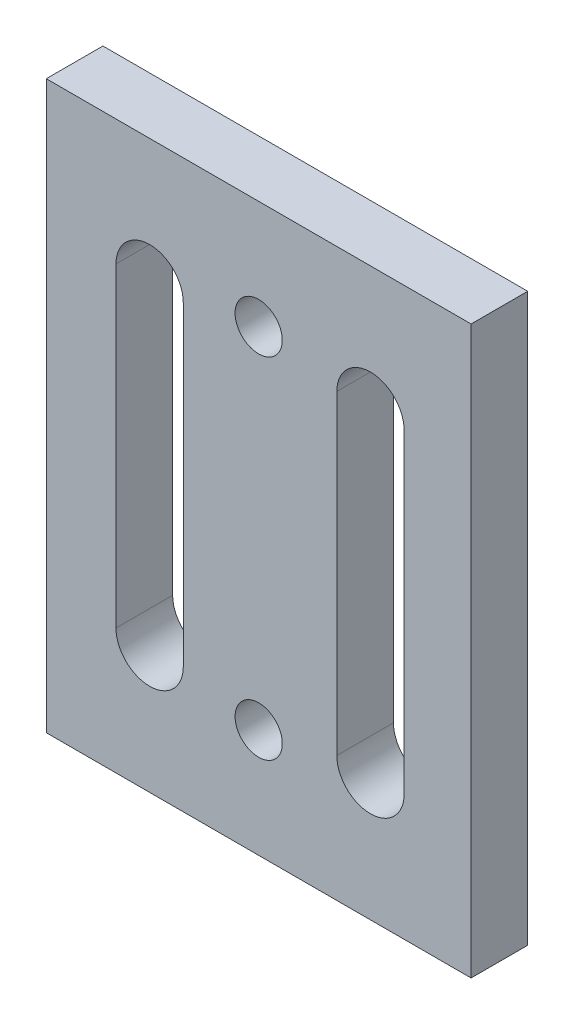
SolidWorks part; units mm, degrees
material "PE High Density"
ref_plane "Front Plane" through (0, 0, 0) normal (0, 0, 1) x (1, 0, 0)
ref_plane "Top Plane" through (0, 0, 0) normal (0, 1, 0) x (1, 0, 0)
ref_plane "Right Plane" through (0, 0, 0) normal (1, 0, 0) x (0, 0, -1)
ref_plane "Plane1" through (0, 0, 0) normal (0, 0, -1) x (-1, 0, 0)
sketch "Sketch1" plane through (0, 0, 0) normal (0, 0, -1) x (-1, 0, 0)
  line L0 (-22.5, 30) -> (-22.5, -30)
  line L1 (-22.5, -30) -> (22.5, -30)
  line L2 (22.5, -30) -> (22.5, 30)
  line L3 (22.5, 30) -> (-22.5, 30)
  line L4 (-11.8412, 16.7) -> (-11.8412, -16.7) construction
  line L5 (-8.2773, 16.7) -> (-8.2773, -16.7)
  line L6 (-15.4052, 16.7) -> (-15.4052, -16.7)
  line L8 (11.5514, 16.7) -> (11.5514, -16.7) construction
  line L9 (7.9874, 16.7) -> (7.9874, -16.7)
  line L10 (15.1153, 16.7) -> (15.1153, -16.7)
  arc A0 (-8.2773, 16.7) -> (-15.4052, 16.7) centre (-11.8412, 16.7) ccw
  circle A1 centre (0, 18.5) radius 2.5
  circle A2 centre (0, -18.5) radius 2.5
  arc A3 (-15.4052, -16.7) -> (-8.2773, -16.7) centre (-11.8412, -16.7) ccw
  arc A4 (7.9874, 16.7) -> (15.1153, 16.7) centre (11.5514, 16.7) cw
  arc A5 (15.1153, -16.7) -> (7.9874, -16.7) centre (11.5514, -16.7) cw
  point P6 (-11.8412, 0)
  point P18 (11.5514, 0)
  dimension "D1" = 11.5
  dimension "D4" = 5
  dimension "D5" = 11.5
  dimension "D6" = 5
  dimension "D2" = 45
  dimension "D3" = 60
extrude "Boss-Extrude1" add sketch "Sketch1" against normal blind 6
